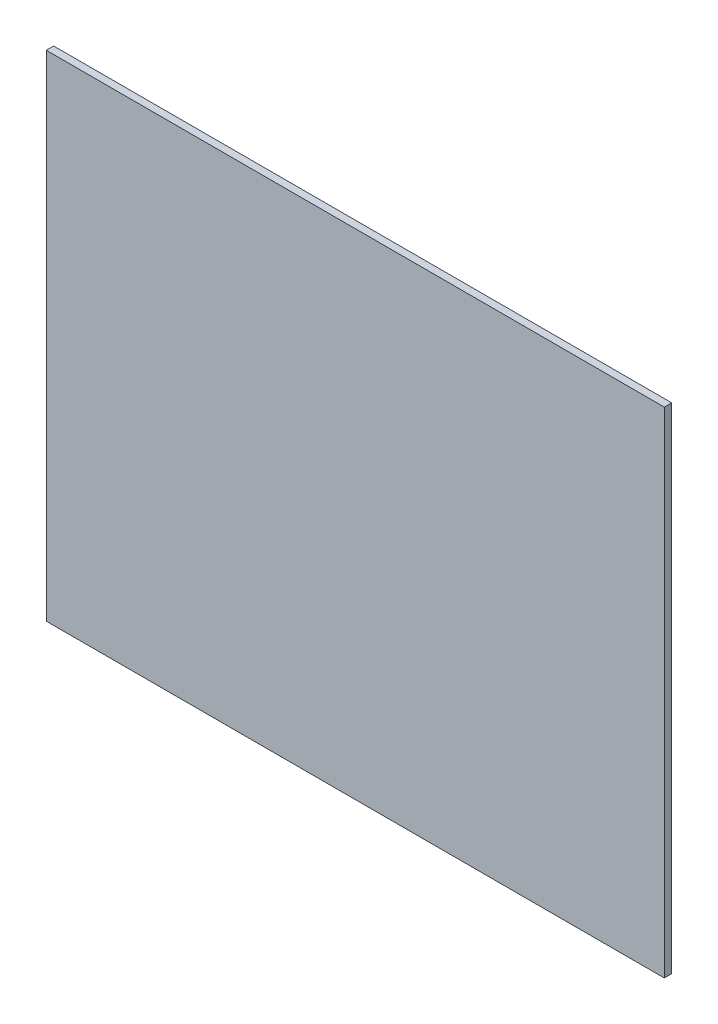
SolidWorks part; units mm, degrees
ref_plane "Front Plane" through (0, 0, 0) normal (0, 0, 1) x (1, 0, 0)
ref_plane "Top Plane" through (0, 0, 0) normal (0, 1, 0) x (1, 0, 0)
ref_plane "Right Plane" through (0, 0, 0) normal (1, 0, 0) x (0, 0, -1)
sketch "Sketch1" plane through (0, 0, 0) normal (0, 0, 1) x (1, 0, 0)
  line L1 (0, 0) -> (500, 0)
  line L2 (0, 0) -> (0, -400)
  line L3 (0, -400) -> (500, -400)
  line L4 (500, 0) -> (500, -400)
  dimension "D1" = 500
  dimension "D2" = 400
extrude "Boss-Extrude1" add sketch "Sketch1" along normal blind 6
sketch "Sketch2" plane through (0, 0, 6) normal (0, 0, 1) x (1, 0, 0)
  line L0 (250, -192.3207) -> (250, -50192.3207) construction
  line L1 (50, -52.3207) -> (450, -52.3207) construction
  line L2 (50, -52.3207) -> (50, -332.3207) construction
  line L3 (50, -332.3207) -> (450, -332.3207) construction
  line L4 (450, -52.3207) -> (450, -332.3207) construction
  line L5 (50, -52.3207) -> (450, -332.3207) construction
  line L6 (50, -332.3207) -> (450, -52.3207) construction
  line L7 (250, -192.3207) -> (50250, -192.3207) construction
  line L8 (250, -192.3207) -> (-49750, -192.3207) construction
  line L9 (450, -332.3207) -> (50, -52.3207) construction
  line L10 (450, -52.3207) -> (50, -332.3207) construction
  line L11 (450, -52.3207) -> (450, -332.3207) construction
  circle A0 centre (50, -52.3207) radius 13.35
  circle A1 centre (90, -52.3207) radius 13.35
  circle A2 centre (130, -52.3207) radius 13.35
  circle A3 centre (170, -52.3207) radius 13.35
  circle A4 centre (210, -52.3207) radius 13.35
  circle A5 centre (250, -52.3207) radius 13.35
  circle A6 centre (290, -52.3207) radius 13.35
  circle A7 centre (330, -52.3207) radius 13.35
  circle A8 centre (370, -52.3207) radius 13.35
  circle A9 centre (410, -52.3207) radius 13.35
  circle A10 centre (450, -52.3207) radius 13.35
  circle A11 centre (50, -92.3207) radius 13.35
  circle A12 centre (50, -132.3207) radius 13.35
  circle A13 centre (50, -172.3207) radius 13.35
  circle A14 centre (50, -212.3207) radius 13.35
  circle A15 centre (50, -252.3207) radius 13.35
  circle A16 centre (50, -292.3207) radius 13.35
  circle A17 centre (50, -332.3207) radius 13.35
  circle A18 centre (450, -332.3207) radius 13.35
  circle A19 centre (450, -292.3207) radius 13.35
  circle A20 centre (450, -252.3207) radius 13.35
  circle A21 centre (450, -212.3207) radius 13.35
  circle A22 centre (450, -172.3207) radius 13.35
  circle A23 centre (450, -132.3207) radius 13.35
  circle A24 centre (450, -92.3207) radius 13.35
  circle A25 centre (450, -52.3207) radius 13.35
  circle A26 centre (410, -332.3207) radius 13.35
  circle A27 centre (370, -332.3207) radius 13.35
  circle A28 centre (330, -332.3207) radius 13.35
  circle A29 centre (290, -332.3207) radius 13.35
  circle A30 centre (250, -332.3207) radius 13.35
  circle A31 centre (210, -332.3207) radius 13.35
  circle A32 centre (170, -332.3207) radius 13.35
  circle A33 centre (130, -332.3207) radius 13.35
  circle A34 centre (90, -332.3207) radius 13.35
  point P0 (250, -192.3207)
  dimension "D3" = 26.7
  dimension "D1" = 400
  dimension "D2" = 280
  dimension "D4" = 11
  dimension "D5" = 8
